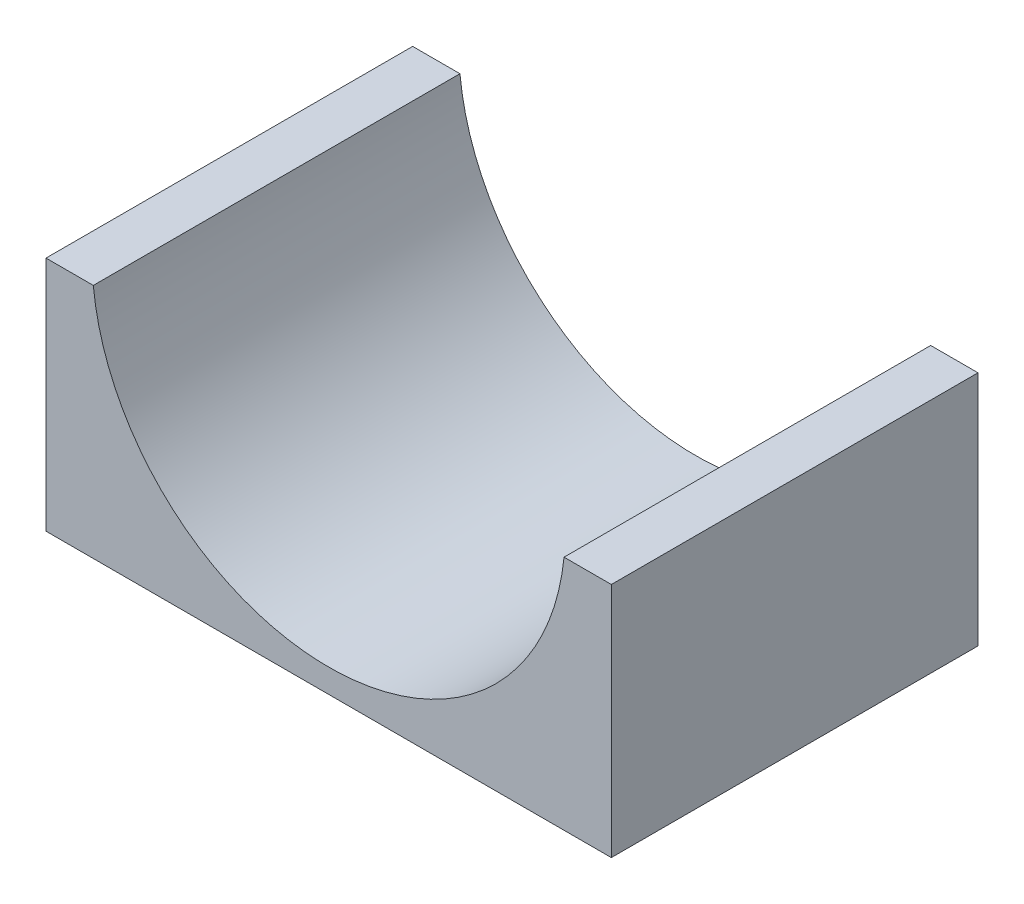
SolidWorks part; units mm, degrees
ref_plane "前视基准面" through (0, 0, 0) normal (0, 0, 1) x (1, 0, 0)
ref_plane "上视基准面" through (0, 0, 0) normal (0, 1, 0) x (1, 0, 0)
ref_plane "右视基准面" through (0, 0, 0) normal (1, 0, 0) x (0, 0, -1)
sketch "草图1" plane through (0, 0, 0) normal (0, 0, 1) x (1, 0, 0)
  line L0 (10.7135, 1.7337) -> (12.7135, 1.7337)
  line L1 (-11.1862, 1.7337) -> (-9.1862, 1.7337)
  line L2 (-11.1862, 1.7337) -> (-11.1862, -8.2663)
  line L3 (-11.1862, -8.2663) -> (12.7135, -8.2663)
  line L4 (12.7135, 1.7337) -> (12.7135, -8.2663)
  arc A0 (-9.1862, 1.7337) -> (10.7135, 1.7337) centre (0.7637, 2.7337) ccw
  point P6 (0.603, 8.6181)
  point P7 (0, 0)
  dimension "D1" = 20
  dimension "D2" = 1
  dimension "D3" = 10
  dimension "D4" = 2
  dimension "D5" = 2
extrude "凸台-拉伸1" add sketch "草图1" along normal blind 15.5
